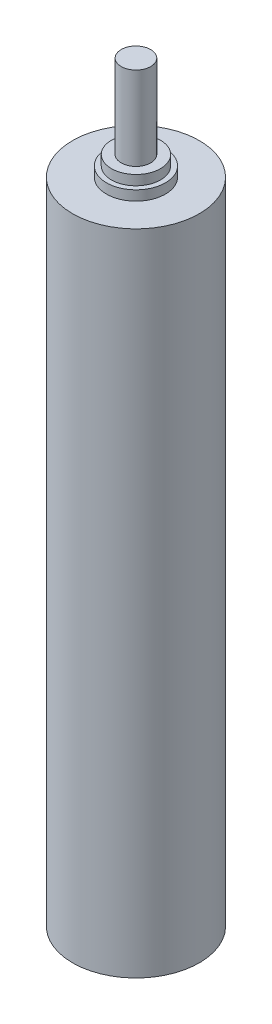
SolidWorks part; units mm, degrees
material "Cast Alloy Steel"
ref_plane "Front Plane" through (0, 0, 0) normal (0, 0, 1) x (1, 0, 0)
ref_plane "Top Plane" through (0, 0, 0) normal (0, 1, 0) x (1, 0, 0)
ref_plane "Right Plane" through (0, 0, 0) normal (1, 0, 0) x (0, 0, -1)
sketch "Sketch1" plane through (0, 0, 0) normal (0, 1, 0) x (1, 0, 0)
  circle A0 centre (0, 0) radius 6.4516
  dimension "D1" = 12.9032
extrude "Boss-Extrude1" add sketch "Sketch1" along normal blind 66.04
sketch "Sketch2" plane through (0, 0, 0) normal (1, 0, 0) x (0, 0, -1)
  line L0 (0, 66.04) -> (0, 76.54)
  line L1 (6.4516, 66.04) -> (-6.4516, 66.04) construction
  line L2 (-3, 66.04) -> (-3, 67.04)
  line L3 (-3, 67.04) -> (-2.5, 67.04)
  line L4 (-2.5, 67.04) -> (-2.5, 68.04)
  line L5 (-2.5, 68.04) -> (-1.5, 68.04)
  line L6 (-1.5, 68.04) -> (-1.5, 76.54)
  line L7 (-1.5, 76.54) -> (0, 76.54)
  line L8 (-3, 66.04) -> (0, 66.04)
  dimension "D1" = 1.5
  dimension "D2" = 2.5
  dimension "D3" = 3
  dimension "D4" = 1
  dimension "D5" = 10.5
revolve "Revolve1" add sketch "Sketch2" angle 360 about L0
